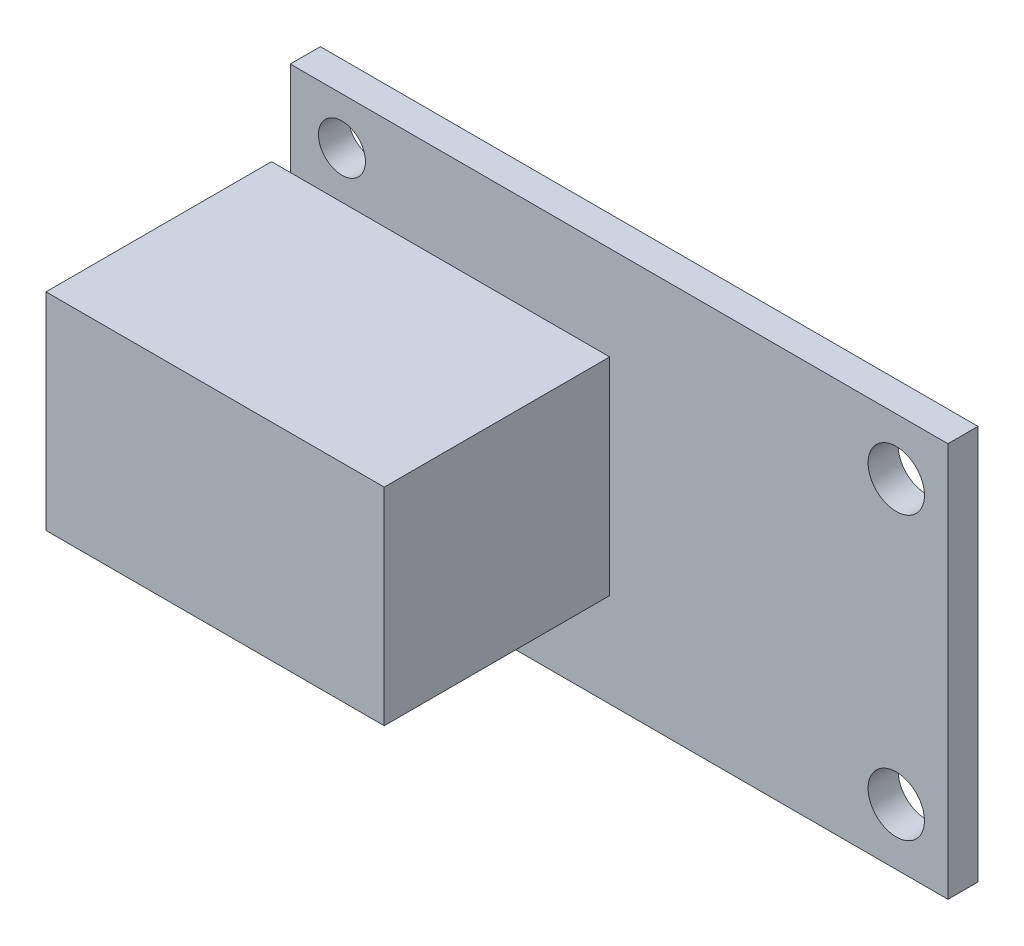
SolidWorks part; units mm, degrees
ref_plane "Front" through (0, 0, 0) normal (0, 0, 1) x (1, 0, 0)
ref_plane "Top" through (0, 0, 0) normal (0, 1, 0) x (1, 0, 0)
ref_plane "Right" through (0, 0, 0) normal (1, 0, 0) x (0, 0, -1)
sketch "Эскиз1" plane through (0, 0, 0) normal (0, 0, 1) x (1, 0, 0)
  line L1 (-17.5, 10.5) -> (17.5, 10.5)
  line L2 (-17.5, 10.5) -> (-17.5, -10.5)
  line L3 (-17.5, -10.5) -> (17.5, -10.5)
  line L4 (17.5, 10.5) -> (17.5, -10.5)
  point P4 (0, -10.5)
  point P5 (17.5, 0)
  dimension "D1" = 21
  dimension "D2" = 35
extrude "Плата" add sketch "Эскиз1" along normal blind 1.6
sketch "Эскиз2" plane through (0, 0, 1.6) normal (0, 0, 1) x (1, 0, 0)
  line L0 (-17.5, 10.5) -> (-17.5, -10.5) construction
  line L1 (-18.5, 5.5) -> (-0.5, 5.5)
  line L2 (-18.5, 5.5) -> (-18.5, -5.5)
  line L3 (-18.5, -5.5) -> (-0.5, -5.5)
  line L4 (-0.5, 5.5) -> (-0.5, -5.5)
  point P6 (-18.5, 0)
  dimension "D1" = 11
  dimension "D2" = 18
  dimension "D3" = 1
extrude "RJ-9" add sketch "Эскиз2" along normal blind 12
sketch "Эскиз3" plane through (0, 0, 1.6) normal (0, 0, 1) x (1, 0, 0)
  line L0 (0, 0) -> (17.5, 0) construction
  line L1 (14.75, 7.5) -> (14.75, -7.5) construction
  line L2 (0, 10.5) -> (0, 0) construction
  line L3 (17.5, 10.5) -> (-17.5, 10.5) construction
  line L4 (17.5, -10.5) -> (17.5, 10.5) construction
  circle A0 centre (-14.75, 8) radius 1.25
  circle A1 centre (14.75, 7.5) radius 1.5
  circle A2 centre (14.75, -7.5) radius 1.5
  circle A3 centre (-14.75, -8) radius 1.25
  point P12 (14.75, 0)
  dimension "D1" = 16
  dimension "D2" = 29.5
  dimension "D3" = 2.5
  dimension "D4" = 3
  dimension "D5" = 15
  dimension "D6" = 14.75
extrude "Крепежные отверстия" cut sketch "Эскиз3" against normal through all
